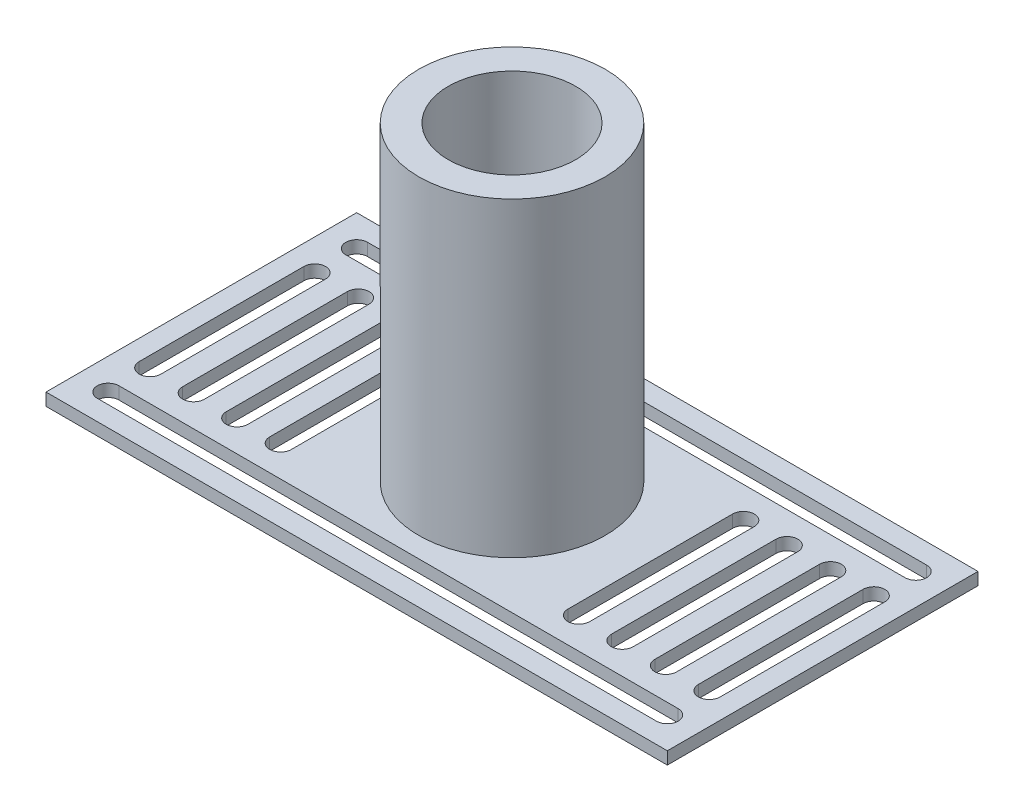
SolidWorks part; units mm, degrees
ref_plane "前视基准面" through (0, 0, 0) normal (0, 0, 1) x (1, 0, 0)
ref_plane "上视基准面" through (0, 0, 0) normal (0, 1, 0) x (1, 0, 0)
ref_plane "右视基准面" through (0, 0, 0) normal (1, 0, 0) x (0, 0, -1)
other "Configuration Table"
sketch "草图1" plane through (0, 0, 0) normal (0, 1, 0) x (1, 0, 0)
  line L1 (1.3106, 0) -> (101.3106, 0)
  line L2 (1.3106, 0) -> (1.3106, 50)
  line L3 (1.3106, 50) -> (101.3106, 50)
  line L4 (101.3106, 0) -> (101.3106, 50)
  dimension "D1" = 50
  dimension "D2" = 100
extrude "凸台-拉伸1" add sketch "草图1" along normal blind 2
sketch "草图2" plane through (0, 2, 0) normal (0, 1, 0) x (1, 0, 0)
  line L0 (1.3106, 25) -> (101.3106, 25) construction
  line L1 (1.3106, 50) -> (1.3106, 0) construction
  line L2 (101.3106, 0) -> (101.3106, 50) construction
  circle A0 centre (51.3106, 25) radius 15
  circle A1 centre (51.3106, 25) radius 10.25
extrude "凸台-拉伸2" add sketch "草图2" along normal blind 50
sketch "草图3" plane through (0, 0, 0) normal (0, -1, 0) x (1, 0, 0)
  line L0 (1.3106, 0) -> (6.3106, 0) construction
  line L1 (1.3106, 0) -> (101.3106, 0) construction
  line L2 (6.3106, 0) -> (6.3106, -5) construction
  line L3 (101.3106, -5) -> (96.3106, -5) construction
  line L4 (101.3106, 0) -> (101.3106, -50) construction
  line L5 (6.3106, -5) -> (96.3106, -5) construction
  line L6 (6.3106, -3.25) -> (96.3106, -3.25)
  line L7 (6.3106, -6.75) -> (96.3106, -6.75)
  line L8 (1.3106, -25) -> (101.3106, -25) construction
  line L9 (1.3106, -50) -> (1.3106, 0) construction
  line L10 (6.3106, -45) -> (96.3106, -45) construction
  line L11 (6.3106, -46.75) -> (96.3106, -46.75)
  line L12 (6.3106, -43.25) -> (96.3106, -43.25)
  line L13 (6.3106, -6.75) -> (6.3106, -11.75) construction
  line L14 (6.3106, -43.25) -> (6.3106, -38.25) construction
  line L15 (6.3106, -11.75) -> (6.3106, -38.25) construction
  line L16 (8.0606, -11.75) -> (8.0606, -38.25)
  line L17 (4.5606, -11.75) -> (4.5606, -38.25)
  line L18 (51.3106, 0) -> (51.3106, -50) construction
  line L19 (101.3106, -50) -> (1.3106, -50) construction
  line L20 (96.3106, -11.75) -> (96.3106, -38.25) construction
  line L21 (94.5606, -11.75) -> (94.5606, -38.25)
  line L22 (98.0606, -11.75) -> (98.0606, -38.25)
  line L23 (13.3106, -11.75) -> (13.3106, -38.25) construction
  line L24 (15.0606, -11.75) -> (15.0606, -38.25)
  line L25 (11.5606, -11.75) -> (11.5606, -38.25)
  line L26 (20.3106, -11.75) -> (20.3106, -38.25) construction
  line L27 (22.0606, -11.75) -> (22.0606, -38.25)
  line L28 (18.5606, -11.75) -> (18.5606, -38.25)
  line L29 (27.3106, -11.75) -> (27.3106, -38.25) construction
  line L30 (29.0606, -11.75) -> (29.0606, -38.25)
  line L31 (25.5606, -11.75) -> (25.5606, -38.25)
  line L32 (89.3106, -11.75) -> (89.3106, -38.25) construction
  line L38 (87.5606, -11.75) -> (87.5606, -38.25)
  line L39 (91.0606, -11.75) -> (91.0606, -38.25)
  line L40 (82.3106, -11.75) -> (82.3106, -38.25) construction
  line L41 (80.5606, -11.75) -> (80.5606, -38.25)
  line L42 (84.0606, -11.75) -> (84.0606, -38.25)
  line L43 (75.3106, -11.75) -> (75.3106, -38.25) construction
  line L44 (73.5606, -11.75) -> (73.5606, -38.25)
  line L45 (77.0606, -11.75) -> (77.0606, -38.25)
  line L64 (34.3106, -11.75) -> (34.3106, -38.25) construction
  line L65 (36.0606, -11.75) -> (36.0606, -38.25)
  line L66 (32.5606, -11.75) -> (32.5606, -38.25)
  line L67 (34.3106, -11.75) -> (34.3106, -38.25) construction
  line L68 (36.0606, -11.75) -> (36.0606, -38.25)
  line L69 (32.5606, -11.75) -> (32.5606, -38.25)
  arc A0 (6.3106, -3.25) -> (6.3106, -6.75) centre (6.3106, -5) ccw
  arc A1 (96.3106, -6.75) -> (96.3106, -3.25) centre (96.3106, -5) ccw
  arc A2 (6.3106, -46.75) -> (6.3106, -43.25) centre (6.3106, -45) cw
  arc A3 (96.3106, -43.25) -> (96.3106, -46.75) centre (96.3106, -45) cw
  arc A4 (8.0606, -11.75) -> (4.5606, -11.75) centre (6.3106, -11.75) ccw
  arc A5 (4.5606, -38.25) -> (8.0606, -38.25) centre (6.3106, -38.25) ccw
  arc A6 (94.5606, -11.75) -> (98.0606, -11.75) centre (96.3106, -11.75) cw
  arc A7 (98.0606, -38.25) -> (94.5606, -38.25) centre (96.3106, -38.25) cw
  arc A8 (15.0606, -11.75) -> (11.5606, -11.75) centre (13.3106, -11.75) ccw
  arc A9 (11.5606, -38.25) -> (15.0606, -38.25) centre (13.3106, -38.25) ccw
  arc A10 (22.0606, -11.75) -> (18.5606, -11.75) centre (20.3106, -11.75) ccw
  arc A11 (18.5606, -38.25) -> (22.0606, -38.25) centre (20.3106, -38.25) ccw
  arc A12 (29.0606, -11.75) -> (25.5606, -11.75) centre (27.3106, -11.75) ccw
  arc A13 (25.5606, -38.25) -> (29.0606, -38.25) centre (27.3106, -38.25) ccw
  arc A18 (87.5606, -11.75) -> (91.0606, -11.75) centre (89.3106, -11.75) cw
  arc A19 (91.0606, -38.25) -> (87.5606, -38.25) centre (89.3106, -38.25) cw
  arc A20 (80.5606, -11.75) -> (84.0606, -11.75) centre (82.3106, -11.75) cw
  arc A21 (84.0606, -38.25) -> (80.5606, -38.25) centre (82.3106, -38.25) cw
  arc A22 (73.5606, -11.75) -> (77.0606, -11.75) centre (75.3106, -11.75) cw
  arc A23 (77.0606, -38.25) -> (73.5606, -38.25) centre (75.3106, -38.25) cw
  arc A38 (36.0606, -11.75) -> (32.5606, -11.75) centre (34.3106, -11.75) ccw
  arc A39 (32.5606, -38.25) -> (36.0606, -38.25) centre (34.3106, -38.25) ccw
  point P10 (51.3106, -5)
  point P21 (51.3106, -45)
  point P30 (6.3106, -25)
  point P41 (96.3106, -25)
  point P50 (13.3106, -25)
  point P56 (20.3106, -25)
  point P63 (27.3106, -25)
  point P71 (89.3106, -25)
  point P76 (34.3106, -25)
  point P84 (82.3106, -25)
  point P91 (75.3106, -25)
  point P98 (34.3106, -25)
  point P105 (34.3106, -25)
  point P112 (34.3106, -25)
  point P119 (34.3106, -25)
  point P126 (34.3106, -25)
  point P133 (34.3106, -25)
  point P140 (34.3106, -25)
  point P147 (34.3106, -25)
  dimension "D3" = 5
  dimension "D4" = 2
  dimension "D1" = 5
  dimension "D2" = 5
  dimension "D5" = 4
  dimension "D6" = 4
extrude "切除-拉伸1" cut sketch "草图3" against normal blind 30
